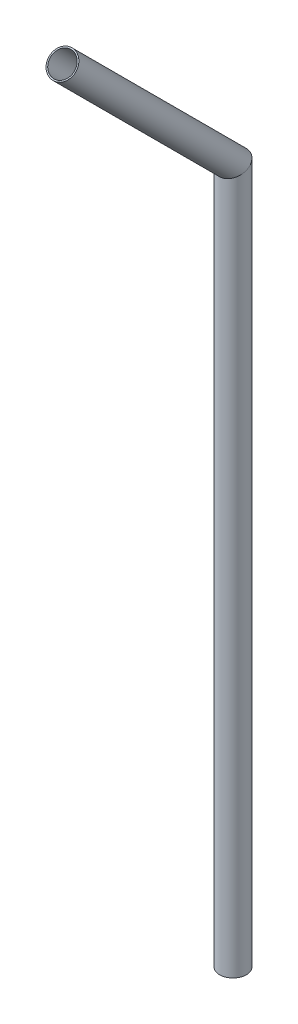
SolidWorks part; units mm, degrees
ref_plane "Plano frontal" through (0, 0, 0) normal (0, 0, 1) x (1, 0, 0)
ref_plane "Plano superior" through (0, 0, 0) normal (0, 1, 0) x (1, 0, 0)
ref_plane "Plano direito" through (0, 0, 0) normal (1, 0, 0) x (0, 0, -1)
sketch "Esboço1" plane through (0, 0, 0) normal (0, 1, 0) x (1, 0, 0)
  circle A0 centre (0, 0) radius 10
  circle A1 centre (0, 0) radius 9
  dimension "D1" = 20
  dimension "D2" = 1
sketch "Esboço2" plane through (0, 0, 0) normal (1, 0, 0) x (0, 0, -1)
  line L0 (0, 0) -> (0, 520)
  line L1 (0, 520) -> (-127.2792, 647.2792)
  dimension "D1" = 520
  dimension "D2" = 180
sweep "Varredura1" add profiles "Esboço1" path "Esboço2"
